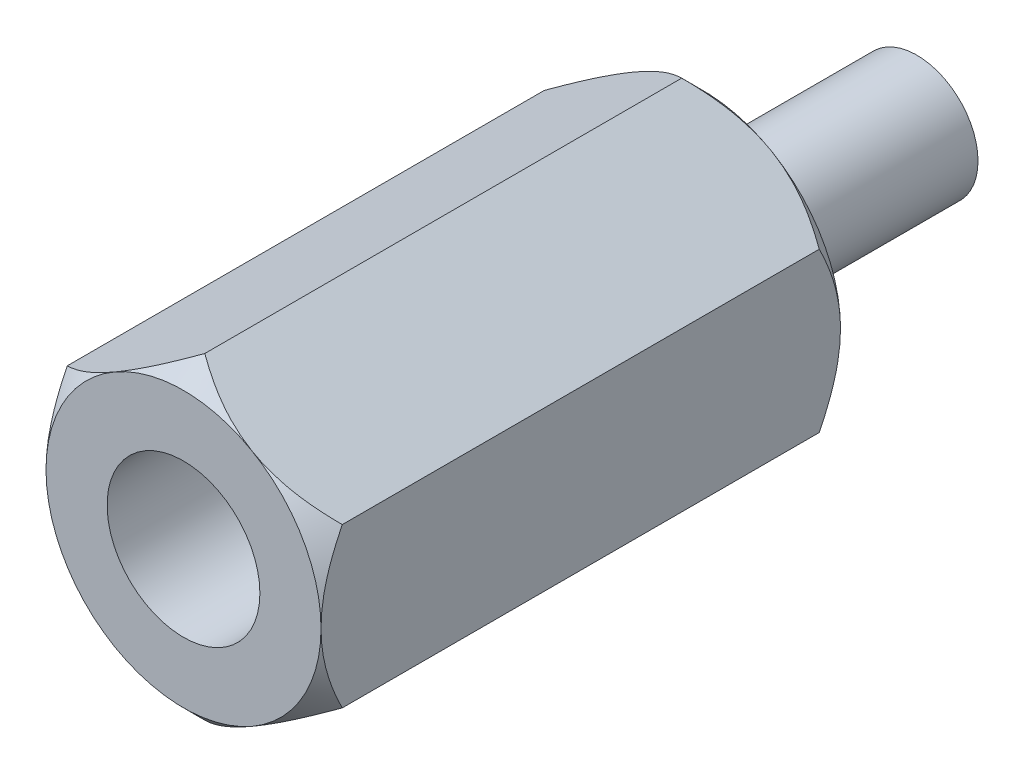
SolidWorks part; units mm, degrees
ref_plane "Front Plane" through (0, 0, 0) normal (0, 0, 1) x (1, 0, 0)
ref_plane "Top Plane" through (0, 0, 0) normal (0, 1, 0) x (1, 0, 0)
ref_plane "Right Plane" through (0, 0, 0) normal (1, 0, 0) x (0, 0, -1)
sketch "Sketch1" plane through (0, 0, 0) normal (0, 0, 1) x (1, 0, 0)
  circle A0 centre (0, 0) radius 1
  dimension "D1" = 2
extrude "Boss-Extrude1" add sketch "Sketch1" along normal blind 3.5
sketch "Sketch2" plane through (0, 0, 3.5) normal (0, 0, 1) x (1, 0, 0)
  line L1 (0, 2.5981) -> (-2.25, 1.299)
  line L2 (-2.25, 1.299) -> (-2.25, -1.299)
  line L3 (-2.25, -1.299) -> (0, -2.5981)
  line L4 (0, -2.5981) -> (2.25, -1.299)
  line L5 (2.25, -1.299) -> (2.25, 1.299)
  line L6 (2.25, 1.299) -> (0, 2.5981)
  circle A0 centre (0, 0) radius 2.25 construction
  dimension "D1" = 4.5
extrude "Boss-Extrude2" add sketch "Sketch2" along normal blind 8.5
sketch "Sketch3" plane through (0, 0, 12) normal (0, 0, 1) x (1, 0, 0)
  circle A0 centre (0, 0) radius 1.25
  dimension "D1" = 2.5
extrude "Cut-Extrude1" cut sketch "Sketch3" against normal blind 4.5
sketch "Sketch4" plane through (0, 0, 12) normal (0, 0, 1) x (1, 0, 0)
  circle A0 centre (0, 0) radius 2.25
extrude "Cut-Extrude2" cut sketch "Sketch4" against normal through all draft 45 flip side to cut
sketch "Sketch6" plane through (0, 0, 3.5) normal (0, 0, -1) x (-1, 0, 0)
  circle A0 centre (0, 0) radius 2.25
extrude "Cut-Extrude3" cut sketch "Sketch6" against normal through all draft 45 flip side to cut
